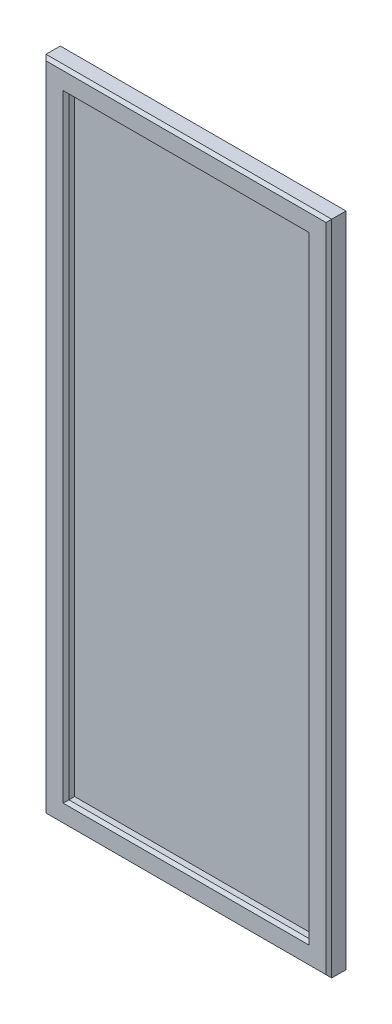
SolidWorks part; units mm, degrees
ref_plane "Спереди" through (0, 0, 0) normal (0, 0, 1) x (1, 0, 0)
ref_plane "Сверху" through (0, 0, 0) normal (0, 1, 0) x (1, 0, 0)
ref_plane "Справа" through (0, 0, 0) normal (1, 0, 0) x (0, 0, -1)
other "Configuration Table"
sketch "Эскиз1" plane through (0, 0, 0) normal (0, 0, 1) x (1, 0, 0)
  line L0 (80, 80) -> (80, 2220)
  line L1 (0, 0) -> (1000, 0)
  line L2 (0, 0) -> (0, 2300)
  line L3 (0, 2300) -> (1000, 2300)
  line L4 (1000, 0) -> (1000, 2300)
  line L5 (80, 2220) -> (920, 2220)
  line L6 (920, 80) -> (920, 2220)
  line L7 (80, 80) -> (920, 80)
  dimension "D1" = 1000
  dimension "D3" = 2300
  dimension "D2" = 80
extrude "Бобышка-Вытянуть1" add sketch "Эскиз1" along normal blind 60
chamfer "Фаска1" distance 10 angle 45 8 edges at (920, 1150, 60) (500, 2220, 60) (80, 1150, 60) (500, 80, 60) (500, 2300, 60) (1000, 1150, 60) (500, 0, 60) (0, 1150, 60)
sketch "Эскиз2" plane through (0, 0, 0) normal (0, 0, -1) x (-1, 0, 0)
  line L1 (-957.0387, 2266.3656) -> (-56.665, 2266.3656)
  line L2 (-957.0387, 2266.3656) -> (-957.0387, 48.4287)
  line L3 (-957.0387, 48.4287) -> (-56.665, 48.4287)
  line L4 (-56.665, 2266.3656) -> (-56.665, 48.4287)
  point P4 (-56.665, 48.4287)
extrude "Бобышка-Вытянуть2" add sketch "Эскиз2" against normal blind 10 from offset 20 separate body
